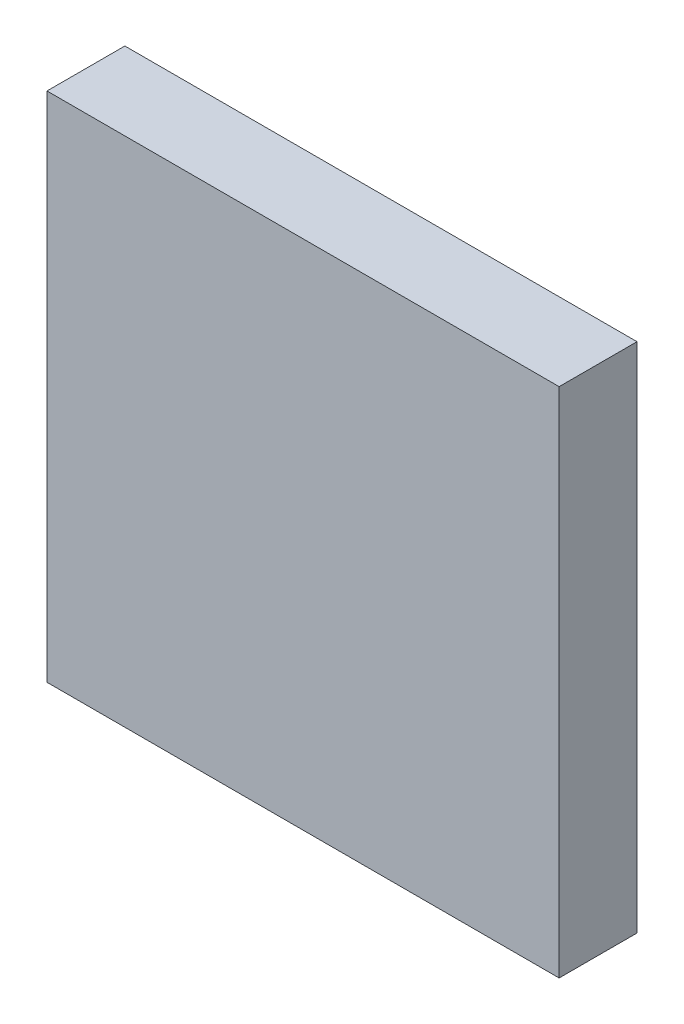
SolidWorks part; units mm, degrees
ref_plane "Front Plane" through (0, 0, 0) normal (0, 0, 1) x (1, 0, 0)
ref_plane "Top Plane" through (0, 0, 0) normal (0, 1, 0) x (1, 0, 0)
ref_plane "Right Plane" through (0, 0, 0) normal (1, 0, 0) x (0, 0, -1)
sketch "Sketch1" plane through (0, 0, 0) normal (0, 0, 1) x (1, 0, 0)
  line L1 (-7.0375, 7.0375) -> (7.0375, 7.0375)
  line L2 (-7.0375, 7.0375) -> (-7.0375, -7.0375)
  line L3 (-7.0375, -7.0375) -> (7.0375, -7.0375)
  line L4 (7.0375, 7.0375) -> (7.0375, -7.0375)
  line L5 (-7.0375, 7.0375) -> (7.0375, -7.0375) construction
  line L6 (-7.0375, -7.0375) -> (7.0375, 7.0375) construction
  point P0 (0, 0)
  dimension "D1" = 14.075
extrude "Boss-Extrude1" add sketch "Sketch1" along normal blind 2.14
